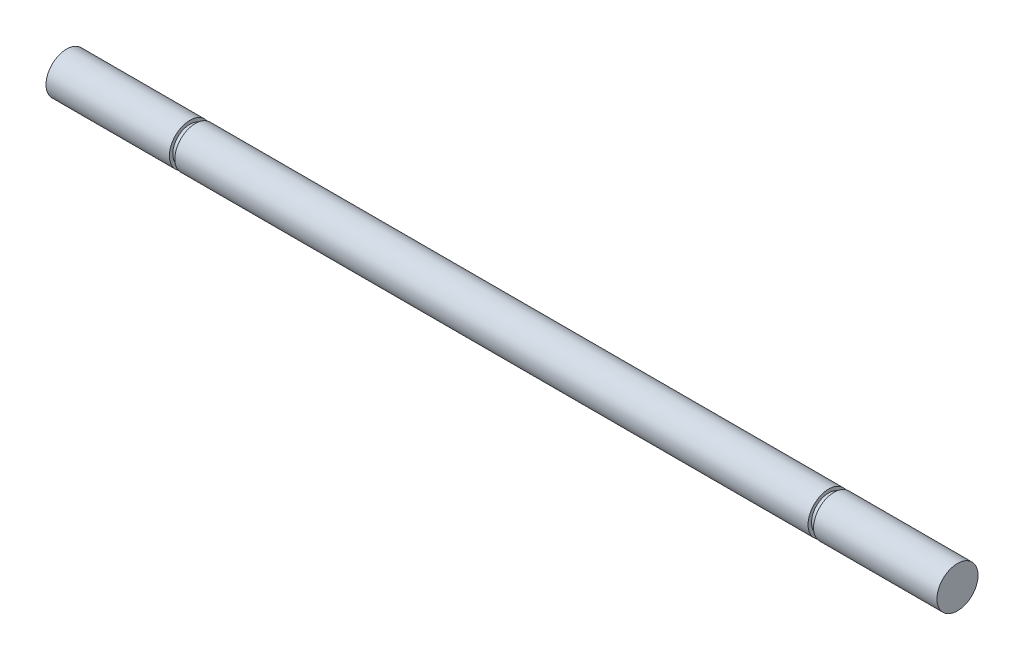
SolidWorks part; units mm, degrees
ref_plane "Ön Düzlem" through (0, 0, 0) normal (0, 0, 1) x (1, 0, 0)
ref_plane "Üst Düzlem" through (0, 0, 0) normal (0, 1, 0) x (1, 0, 0)
ref_plane "Sağ Düzlem" through (0, 0, 0) normal (1, 0, 0) x (0, 0, -1)
sketch "Sketch2" plane through (0, 0, 0) normal (0, 0, 1) x (1, 0, 0)
  line L0 (0, 0) -> (130, 0)
  line L2 (0, 0) -> (0, -3)
  line L3 (0, -3) -> (18, -3)
  line L4 (130, 0) -> (130, -3)
  line L5 (18.8, -3) -> (111.2, -3)
  line L7 (18, -2.5) -> (18, -3)
  line L9 (18.8, -2.5) -> (18.8, -3)
  line L10 (130, -3) -> (112, -3)
  line L11 (18.8, -3) -> (18.8, -2.5)
  line L12 (18.8, -2.5) -> (18, -2.5)
  line L13 (18, -3) -> (18, -2.5)
  line L14 (112, -3) -> (130, -3)
  line L16 (112, -3) -> (112, -2.5)
  line L17 (112, -2.5) -> (111.2, -2.5)
  line L18 (111.2, -3) -> (111.2, -2.5)
  dimension "D1" = 3
  dimension "D2" = 130
  dimension "D4" = 0.8
  dimension "D5" = 0.5
  dimension "D6" = 18
  dimension "D7" = 0.5
  dimension "D8" = 0.8
revolve "Revolve1" add sketch "Sketch2" angle 360 about L0
